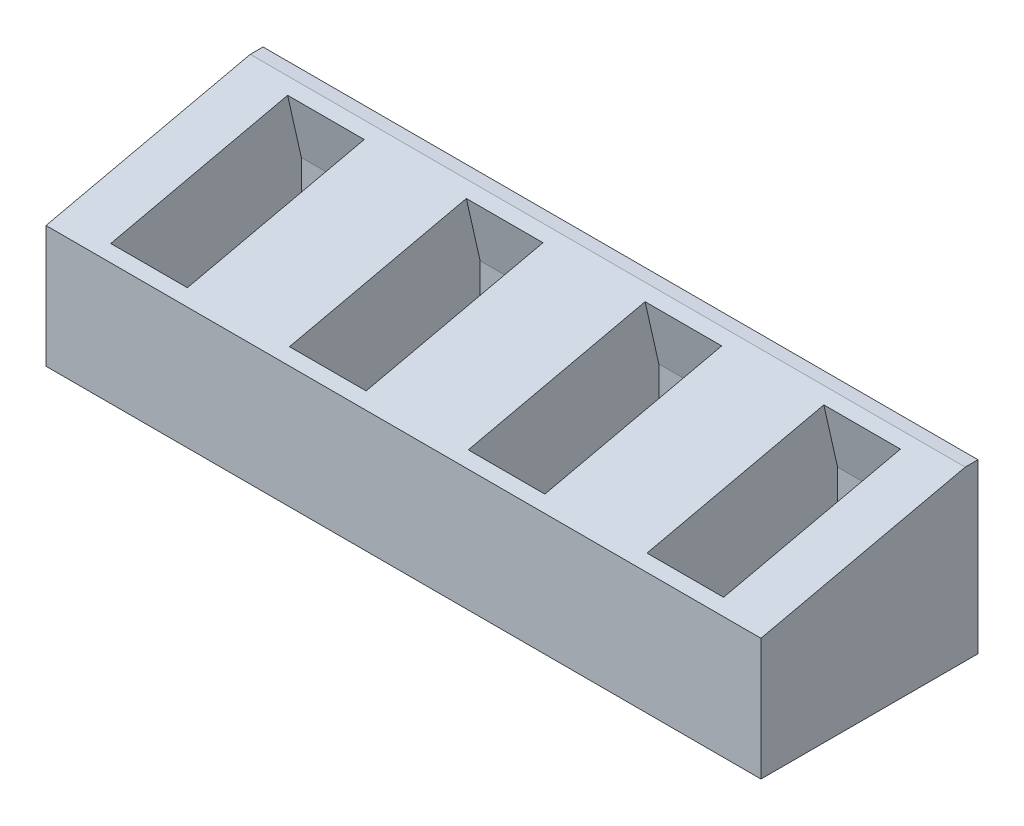
SolidWorks part; units mm, degrees
ref_plane "Front Plane" through (0, 0, 0) normal (0, 0, 1) x (1, 0, 0)
ref_plane "Top Plane" through (0, 0, 0) normal (0, 1, 0) x (1, 0, 0)
ref_plane "Right Plane" through (0, 0, 0) normal (1, 0, 0) x (0, 0, -1)
sketch "Sketch1" plane through (0, 0, 0) normal (0, 0, 1) x (1, 0, 0)
  line L0 (0, 0) -> (711.2, 0)
  line L1 (0, 0) -> (0, 167.132)
  line L2 (0, 167.132) -> (711.2, 167.132)
  line L3 (711.2, 167.132) -> (711.2, 0)
  dimension "D1" = 711.2
  dimension "D2" = 167.132
  dimension "D3" = 167.132
extrude "Boss-Extrude2" add sketch "Sketch1" along normal blind 203.2 contours L2 L3 L0 L1
sketch "Sketch5" plane through (711.2, 0, 0) normal (1, 0, 0) x (0, 0, -1)
  line L1 (0, 167.132) -> (-203.2, 121.2757)
  line L2 (-203.2, 167.132) -> (-203.2, 0) construction
  line L3 (-203.2, 121.2757) -> (-203.2, 167.132)
  line L4 (-203.2, 167.132) -> (0, 167.132)
extrude "Cut-Extrude3" cut sketch "Sketch5" against normal blind 919.48
sketch "Sketch6" plane through (0, 159.0329, 35.8891) normal (0, 0.9755, 0.2201) x (1, 0, 0)
  line L0 (355.6, 36.7916) -> (355.6, -171.5184) construction
  line L1 (0, 36.7916) -> (711.2, 36.7916) construction
  line L2 (0, -171.5184) -> (711.2, -171.5184) construction
  line L3 (0, -67.3634) -> (177.8, -67.3634) construction
  line L4 (177.8, 36.7916) -> (177.8, -171.5184) construction
  line L5 (0, 36.7916) -> (0, -171.5184) construction
  line L7 (304.8, 22.8066) -> (304.8, -157.5334)
  line L8 (50.8, 22.8066) -> (127, 22.8066)
  line L9 (50.8, 22.8066) -> (50.8, -157.5334)
  line L10 (50.8, -157.5334) -> (127, -157.5334)
  line L11 (127, 22.8066) -> (127, -157.5334)
  line L12 (50.8, 22.8066) -> (127, -157.5334) construction
  line L13 (50.8, -157.5334) -> (127, 22.8066) construction
  line L14 (304.8, -157.5334) -> (228.6, -157.5334)
  line L15 (228.6, 22.8066) -> (228.6, -157.5334)
  line L16 (304.8, 22.8066) -> (228.6, 22.8066)
  line L17 (406.4, 22.8066) -> (482.6, 22.8066)
  line L18 (482.6, 22.8066) -> (482.6, -157.5334)
  line L19 (406.4, 22.8066) -> (406.4, -157.5334)
  line L20 (406.4, -157.5334) -> (482.6, -157.5334)
  line L21 (660.4, -157.5334) -> (584.2, -157.5334)
  line L22 (660.4, 22.8066) -> (660.4, -157.5334)
  line L23 (584.2, 22.8066) -> (584.2, -157.5334)
  line L24 (660.4, 22.8066) -> (584.2, 22.8066)
  point P13 (88.9, -67.3634)
  dimension "D1" = 76.2
  dimension "D2" = 180.34
extrude "Cut-Extrude5" cut sketch "Sketch6" against normal blind 114.3
sketch "Sketch7" plane through (0, 0, 0) normal (0, 0, -1) x (-1, 0, 0)
  line L1 (-711.2, 167.132) -> (0, 167.132)
  line L2 (-711.2, 167.132) -> (-711.2, 0)
  line L3 (-711.2, 0) -> (0, 0)
  line L4 (0, 167.132) -> (0, 0)
extrude "Boss-Extrude3" add sketch "Sketch7" along normal blind 12.7
